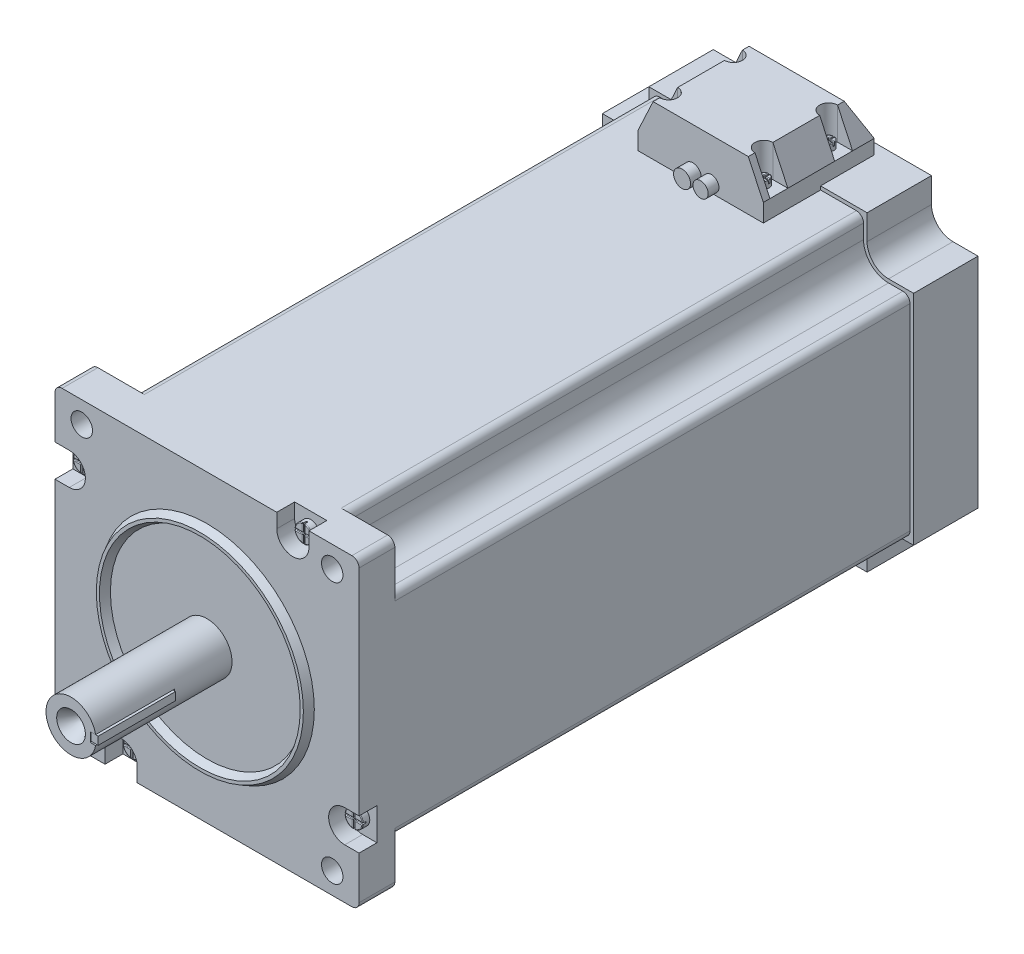
SolidWorks part; units mm, degrees
ref_plane "Front Plane" through (0, 0, 0) normal (0, 0, 1) x (1, 0, 0)
ref_plane "Top Plane" through (0, 0, 0) normal (0, 1, 0) x (1, 0, 0)
ref_plane "Right Plane" through (0, 0, 0) normal (1, 0, 0) x (0, 0, -1)
sketch "Sketch1" plane through (0, 0, 0) normal (0, 0, 1) x (1, 0, 0)
  line L0 (42.5, 85) -> (42.5, 0) construction
  line L1 (13, 0) -> (72, 0)
  line L2 (0, 13) -> (0, 72)
  line L3 (13, 85) -> (72, 85)
  line L4 (85, 13) -> (85, 72)
  line L7 (0, 72) -> (6, 72)
  line L8 (13, 85) -> (13, 79)
  line L9 (0, 42.5) -> (85, 42.5) construction
  line L10 (72, 85) -> (72, 79)
  line L11 (85, 72) -> (79, 72)
  line L14 (13, 0) -> (13, 6)
  line L15 (0, 13) -> (6, 13)
  line L20 (85, 13) -> (79, 13)
  line L21 (72, 0) -> (72, 6)
  arc A0 (13, 79) -> (6, 72) centre (6, 79) cw
  arc A1 (72, 79) -> (79, 72) centre (79, 79) ccw
  arc A2 (13, 6) -> (6, 13) centre (6, 6) ccw
  arc A3 (72, 6) -> (79, 13) centre (79, 6) cw
  point P10 (13, 72)
  point P20 (72, 72)
  point P26 (13, 13)
  point P32 (72, 13)
  dimension "D5" = 7
  dimension "D3" = 13
  dimension "D4" = 13
extrude "Boss-Extrude1" add sketch "Sketch1" along normal blind 144
sketch "Sketch2" plane through (0, 0, 0) normal (0, 0, -1) x (-1, 0, 0)
  line L0 (1, 73) -> (-6, 73)
  line L1 (-12, 79) -> (-12, 86)
  line L2 (-12, 86) -> (-73, 86)
  line L3 (-73, 86) -> (-73, 79)
  line L4 (-79, 73) -> (-86, 73)
  line L5 (-86, 73) -> (-86, 12)
  line L6 (-86, 12) -> (-79, 12)
  line L7 (-73, 6) -> (-73, -1)
  line L8 (-73, -1) -> (-12, -1)
  line L9 (-12, -1) -> (-12, 6)
  line L10 (-6, 12) -> (1, 12)
  line L11 (1, 12) -> (1, 73)
  line L12 (0, 72) -> (-6, 72)
  line L13 (-13, 79) -> (-13, 85)
  line L14 (-13, 85) -> (-72, 85)
  line L15 (-72, 85) -> (-72, 79)
  line L16 (-79, 72) -> (-85, 72)
  line L17 (-85, 72) -> (-85, 13)
  line L18 (-85, 13) -> (-79, 13)
  line L19 (-72, 6) -> (-72, 0)
  line L20 (-72, 0) -> (-13, 0)
  line L21 (-13, 0) -> (-13, 6)
  line L22 (-6, 13) -> (0, 13)
  line L23 (0, 13) -> (0, 72)
  line L24 (0, 72) -> (-6, 72)
  line L25 (-13, 79) -> (-13, 85)
  line L26 (-13, 85) -> (-72, 85)
  line L27 (-72, 85) -> (-72, 79)
  line L28 (-79, 72) -> (-85, 72)
  line L29 (-85, 72) -> (-85, 13)
  line L30 (-85, 13) -> (-79, 13)
  line L31 (-72, 6) -> (-72, 0)
  line L32 (-72, 0) -> (-13, 0)
  line L33 (-13, 0) -> (-13, 6)
  line L34 (-6, 13) -> (0, 13)
  line L35 (0, 13) -> (0, 72)
  arc A0 (-12, 79) -> (-6, 73) centre (-6, 79) ccw
  arc A1 (-79, 73) -> (-73, 79) centre (-79, 79) ccw
  arc A2 (-73, 6) -> (-79, 12) centre (-79, 6) ccw
  arc A3 (-6, 12) -> (-12, 6) centre (-6, 6) ccw
  arc A4 (-13, 79) -> (-6, 72) centre (-6, 79) ccw
  arc A5 (-79, 72) -> (-72, 79) centre (-79, 79) ccw
  arc A6 (-72, 6) -> (-79, 13) centre (-79, 6) ccw
  arc A7 (-6, 13) -> (-13, 6) centre (-6, 6) ccw
  arc A8 (-13, 79) -> (-6, 72) centre (-6, 79) ccw
  arc A9 (-79, 72) -> (-72, 79) centre (-79, 79) ccw
  arc A10 (-72, 6) -> (-79, 13) centre (-79, 6) ccw
  arc A11 (-6, 13) -> (-13, 6) centre (-6, 6) ccw
  line M17 (0, 72) -> (-6, 72)
  arc M18 (-6, 72) -> (-13, 79) centre (-6, 79) cw
  line M19 (-13, 79) -> (-13, 85)
  line M20 (-13, 85) -> (-72, 85)
  line M21 (-72, 85) -> (-72, 79)
  arc M22 (-72, 79) -> (-79, 72) centre (-79, 79) cw
  line M23 (-79, 72) -> (-85, 72)
  line M24 (-85, 72) -> (-85, 13)
  line M25 (-85, 13) -> (-79, 13)
  arc M26 (-79, 13) -> (-72, 6) centre (-79, 6) cw
  line M27 (-72, 6) -> (-72, 0)
  line M28 (-72, 0) -> (-13, 0)
  line M29 (-13, 0) -> (-13, 6)
  arc M30 (-13, 6) -> (-6, 13) centre (-6, 6) cw
  line M31 (-6, 13) -> (0, 13)
  line M32 (0, 13) -> (0, 72)
  dimension "D1" = 0
  dimension "D2" = 1
extrude "Boss-Extrude2" add sketch "Sketch2" along normal blind 18 contours M32 M17 M18 M19 M20 M21 M22 M23 M24 M25 M26 M27 M28 M29 M30 M31 | A3 L10 L11 L0 A0 L1 L2 L3 A1 L4 L5 L6 A2 L7 L8 L9 M17 M32 M31 M30 M29 M28 M27 M26 M25 M24 M23 M22 M21 M20 M19 M18
sketch "Sketch4" plane through (0, 0, 144) normal (0, 0, 1) x (1, 0, 0)
  line L1 (0, 0) -> (85, 0)
  line L2 (0, 0) -> (0, 85)
  line L3 (0, 85) -> (85, 85)
  line L4 (85, 0) -> (85, 85)
  line L5 (0, 0) -> (85, 85) construction
  line L6 (0, 85) -> (85, 0) construction
  point P0 (42.5, 42.5)
extrude "Boss-Extrude3" add sketch "Sketch4" along normal blind 10
sketch "Sketch5" plane through (0, 0, 154) normal (0, 0, 1) x (1, 0, 0)
  line L0 (42.5, 85) -> (42.5, -1) construction
  line L1 (85, 85) -> (0, 85) construction
  line L2 (73, -1) -> (12, -1) construction
  line L3 (0, 42.5) -> (85, 42.5) construction
  line L4 (0, 72) -> (0, 13) construction
  line L5 (85, 0) -> (85, 85) construction
  circle A0 centre (7.5, 79) radius 3
  circle A1 centre (77.5, 79) radius 3
  circle A2 centre (77.5, 6) radius 3
  circle A3 centre (7.5, 6) radius 3
  dimension "D1" = 6
  dimension "D2" = 35
  dimension "D3" = 6
extrude "Cut-Extrude1" cut sketch "Sketch5" against normal up to surface (10 mm away) up to face at (6.6899, 78.3101, 144)
sketch "Sketch6" plane through (0, 0, 154) normal (0, 0, 1) x (1, 0, 0)
  line L0 (0, 71) -> (4, 71)
  line L1 (0, 72) -> (0, 13) construction
  line L2 (85, 85) -> (0, 85) construction
  line L3 (0, 62) -> (4, 62)
  line L4 (0, 71) -> (0, 62)
  line L5 (62, 85) -> (62, 81)
  line L6 (71, 85) -> (71, 81)
  line L7 (71, 85) -> (62, 85)
  line L8 (85, 23) -> (81, 23)
  line L9 (85, 14) -> (81, 14)
  line L10 (85, 14) -> (85, 23)
  line L11 (23, 0) -> (23, 4)
  line L12 (14, 0) -> (14, 4)
  line L13 (14, 0) -> (23, 0)
  arc A0 (4, 62) -> (4, 71) centre (4, 66.5) ccw
  circle A1 centre (42.5, 42.5) radius 6.3473 construction
  arc A2 (62, 81) -> (71, 81) centre (66.5, 81) ccw
  arc A3 (81, 23) -> (81, 14) centre (81, 18.5) ccw
  arc A4 (23, 4) -> (14, 4) centre (18.5, 4) ccw
  point P29 (42.5, 42.5)
  dimension "D1" = 14
  dimension "D3" = 4
  dimension "D2" = 9
  dimension "D4" = 4
extrude "Cut-Extrude2" cut sketch "Sketch6" against normal blind 5
sketch "Sketch7" plane through (0, 0, 154) normal (0, 0, 1) x (1, 0, 0)
  circle A0 centre (42.5, 42.5) radius 30
  circle A1 centre (42.5, 42.5) radius 27
  dimension "D1" = 60
  dimension "D2" = 3
extrude "Boss-Extrude4" add sketch "Sketch7" along normal blind 2 draft 28
sketch "Sketch8" plane through (0, 0, 154) normal (0, 0, 1) x (1, 0, 0)
  circle A0 centre (42.5, 42.5) radius 7
  dimension "D1" = 14
extrude "Boss-Extrude5" add sketch "Sketch8" along normal blind 38
sketch "Sketch9" plane through (0, 0, 192) normal (0, 0, 1) x (1, 0, 0)
  circle A0 centre (42.5, 42.5) radius 4.0146
extrude "Cut-Extrude3" cut sketch "Sketch9" against normal blind 5 draft 32
sketch "Sketch10" plane through (0, 0, 192) normal (0, 0, 1) x (1, 0, 0)
  line L1 (47.8876, 43.8537) -> (49.7957, 43.8537)
  line L2 (47.8876, 43.8537) -> (47.8876, 41.2149)
  line L3 (47.8876, 41.2149) -> (49.7957, 41.2149)
  line L4 (49.7957, 43.8537) -> (49.7957, 41.2149)
extrude "Cut-Extrude4" cut sketch "Sketch10" against normal blind 22
sketch "Sketch11" plane through (47.8876, 0, 0) normal (1, 0, 0) x (0, 0, -1)
  line L8 (-191.8, 43.6537) -> (-191.8, 41.4149)
  line L9 (-191.8, 41.4149) -> (-170.2, 41.4149)
  line L10 (-170.2, 41.4149) -> (-170.2, 43.6537)
  line L11 (-170.2, 43.6537) -> (-191.8, 43.6537)
  line L12 (-191.8, 43.6537) -> (-191.8, 41.4149)
  line L13 (-191.8, 41.4149) -> (-170.2, 41.4149)
  line L14 (-170.2, 41.4149) -> (-170.2, 43.6537)
  line L15 (-170.2, 43.6537) -> (-191.8, 43.6537)
  dimension "D1" = 0.2
extrude "Boss-Extrude6" add sketch "Sketch11" along normal blind 2
fillet "Fillet1" radius 2 4 edges at (85, 0, 149) (0, 0, 149) (0, 85, 149) (85, 85, 149)
fillet "Fillet2" radius 2 8 edges at (0, 13, 72) (13, 0, 72) (72, 0, 72) (85, 13, 72) (0, 72, 72) (85, 72, 72) (13, 85, 72) (72, 85, 72)
sketch "Sketch12" plane through (0, 0, 149) normal (0, 0, 1) x (1, 0, 0)
  circle A0 centre (66.5, 80.4984) radius 2.5
  circle A1 centre (80.4984, 18.5) radius 2.5
  circle A2 centre (18.5, 4.5016) radius 2.5
  circle A3 centre (4.5016, 66.5) radius 2.5
  point P11 (42.5, 42.5)
  dimension "D1" = 5
  dimension "D2" = 4
extrude "Boss-Extrude7" add sketch "Sketch12" along normal blind 2
sketch "Sketch13" plane through (0, 0, 151) normal (0, 0, 1) x (1, 0, 0)
  line L0 (66.5, 82.9984) -> (66.5, 77.9984) construction
  line L1 (64, 80.4984) -> (69, 80.4984) construction
  line L2 (64, 80.2984) -> (66.3, 80.2984)
  line L3 (66.3, 82.9984) -> (66.3, 80.6984)
  line L4 (64, 80.6984) -> (66.3, 80.6984)
  line L5 (66.7, 82.9984) -> (66.7, 80.6984)
  line L6 (66.3, 80.2984) -> (66.3, 77.9984)
  line L7 (66.7, 80.6984) -> (69, 80.6984)
  line L8 (66.3, 82.9984) -> (66.3, 77.9984) construction
  line L9 (66.7, 80.2984) -> (66.7, 77.9984)
  line L10 (64, 80.6984) -> (69, 80.6984) construction
  line L11 (66.7, 80.2984) -> (69, 80.2984)
  line L12 (66.7, 82.9984) -> (66.7, 77.9984) construction
  line L13 (82.9984, 18.3) -> (80.6984, 18.3)
  line L14 (64, 80.2984) -> (69, 80.2984) construction
  line L15 (80.6984, 18.3) -> (80.6984, 16)
  line L16 (80.2984, 18.3) -> (80.2984, 16)
  line L17 (80.2984, 18.3) -> (77.9984, 18.3)
  line L18 (80.2984, 18.7) -> (77.9984, 18.7)
  line L19 (80.2984, 21) -> (80.2984, 18.7)
  line L20 (80.6984, 21) -> (80.6984, 18.7)
  line L21 (82.9984, 18.7) -> (80.6984, 18.7)
  line L22 (18.3, 2.0016) -> (18.3, 4.3016)
  line L23 (18.3, 4.3016) -> (16, 4.3016)
  line L24 (18.3, 4.7016) -> (16, 4.7016)
  line L25 (18.3, 4.7016) -> (18.3, 7.0016)
  line L26 (18.7, 4.7016) -> (18.7, 7.0016)
  line L27 (21, 4.7016) -> (18.7, 4.7016)
  line L28 (21, 4.3016) -> (18.7, 4.3016)
  line L29 (18.7, 2.0016) -> (18.7, 4.3016)
  line L30 (2.0016, 66.7) -> (4.3016, 66.7)
  line L31 (4.3016, 66.7) -> (4.3016, 69)
  line L32 (4.7016, 66.7) -> (4.7016, 69)
  line L33 (4.7016, 66.7) -> (7.0016, 66.7)
  line L34 (4.7016, 66.3) -> (7.0016, 66.3)
  line L35 (4.7016, 64) -> (4.7016, 66.3)
  line L36 (4.3016, 64) -> (4.3016, 66.3)
  line L37 (2.0016, 66.3) -> (4.3016, 66.3)
  circle A0 centre (66.5, 80.4984) radius 2.5 construction
  circle A1 centre (66.5, 80.4984) radius 2.5 construction
  circle A2 centre (80.4984, 18.5) radius 2.5
  circle A3 centre (66.5, 80.4984) radius 2.5
  circle A4 centre (66.5, 80.4984) radius 2.5
  circle A5 centre (18.5, 4.5016) radius 2.5
  circle A6 centre (4.5016, 66.5) radius 2.5
  point P69 (42.5, 42.5)
  circle M4 centre (66.5, 80.4984) radius 2.5
  dimension "D1" = 0.2
  dimension "D2" = 0.2
  dimension "D3" = 0
  dimension "D4" = 4
extrude "Cut-Extrude5" cut sketch "Sketch13" against normal blind 1 contours L9 L11 L7 L5 L3 L4 L2 L6 M4 | L32 A6 L31 L30 L37 L36 L35 L34 L33 | L26 A5 L25 L24 L23 L22 L29 L28 L27 | L20 A2 L19 L18 L17 L16 L15 L13 L21
fillet "Fillet3" radius 0.2 48 edges at (3.1556, 66.3, 151) (4.3016, 65.154, 151) (2.7338, 64.7322, 151) (6.2694, 64.7322, 151) (4.7016, 65.154, 151) (5.8476, 66.3, 151) (6.2694, 68.2678, 151) (5.8476, 66.7, 151) (4.7016, 67.846, 151) (4.3016, 67.846, 151) (3.1556, 66.7, 151) (2.7338, 68.2678, 151) (20.2678, 6.2694, 151) (19.846, 4.7016, 151) (18.7, 5.8476, 151) (18.7, 3.1556, 151) (19.846, 4.3016, 151) (20.2678, 2.7338, 151) (17.154, 4.3016, 151) (18.3, 3.1556, 151) (16.7322, 2.7338, 151) (16.7322, 6.2694, 151) (18.3, 5.8476, 151) (17.154, 4.7016, 151) (78.7306, 16.7322, 151) (79.1524, 18.3, 151) (80.2984, 17.154, 151) (80.6984, 17.154, 151) (81.8444, 18.3, 151) (82.2662, 16.7322, 151) (81.8444, 18.7, 151) (80.6984, 19.846, 151) (82.2662, 20.2678, 151) (78.7306, 20.2678, 151) (80.2984, 19.846, 151) (79.1524, 18.7, 151) (68.2678, 78.7306, 151) (66.7, 79.1524, 151) (67.846, 80.2984, 151) (64.7322, 78.7306, 151) (65.154, 80.2984, 151) (66.3, 79.1524, 151) (66.3, 81.8444, 151) (65.154, 80.6984, 151) (64.7322, 82.2662, 151) (67.846, 80.6984, 151) (66.7, 81.8444, 151) (68.2678, 82.2662, 151)
sketch "Sketch14" plane through (0, 85, 0) normal (0, 1, 0) x (1, 0, 0)
  line L0 (42.5, 18) -> (42.5, -26.4947) construction
  line L1 (12, 18) -> (73, 18) construction
  line L3 (25, 15) -> (60, 15)
  line L4 (25, 15) -> (25, -16)
  line L5 (25, -16) -> (60, -16)
  line L6 (60, 15) -> (60, -16)
  line L7 (25, 15) -> (60, -16) construction
  line L8 (25, -16) -> (60, 15) construction
  point P4 (42.5, -0.5)
  dimension "D1" = 35
  dimension "D2" = 31
  dimension "D3" = 3
extrude "Boss-Extrude8" add sketch "Sketch14" along normal blind 5
sketch "Sketch15" plane through (0, 90, 0) normal (0, 1, 0) x (1, 0, 0)
  line L4 (60, -16) -> (60, 15)
  line L5 (60, 15) -> (25, 15)
  line L6 (25, 15) -> (25, -16)
  line L7 (25, -16) -> (60, -16)
  line L8 (60, -16) -> (60, 15)
  line L9 (60, 15) -> (25, 15)
  line L10 (25, 15) -> (25, -16)
  line L11 (25, -16) -> (60, -16)
  dimension "D1" = 0
extrude "Boss-Extrude9" add sketch "Sketch15" along normal blind 9 draft 25
sketch "Sketch16" plane through (0, 99, 0) normal (0, 1, 0) x (1, 0, 0)
  line L0 (25, 0) -> (25, -16) construction
  line L1 (25, -11.8032) -> (60, -11.8032)
  line L2 (25, -11.8032) -> (25, -16)
  line L3 (25, -16) -> (60, -16)
  line L4 (60, -11.8032) -> (60, -16)
  line L5 (29.1968, -11.8032) -> (55.8032, -11.8032) construction
extrude "Boss-Extrude10" add sketch "Sketch16" against normal up to surface (14 mm away) up to face at (48.5, 85, 95.125)
sketch "Sketch17" plane through (0, 0, 11.8032) normal (0, 0, -1) x (-1, 0, 0)
  line L3 (-60, 90) -> (-55.8032, 99)
  line L4 (-55.8032, 99) -> (-60, 99)
  line L5 (-60, 99) -> (-60, 90)
  line L6 (-60, 90) -> (-55.8032, 99)
  line L7 (-55.8032, 99) -> (-60, 99)
  line L8 (-60, 99) -> (-60, 90)
  line L9 (-29.1968, 99) -> (-25, 90)
  line L10 (-25, 90) -> (-25, 99)
  line L11 (-25, 99) -> (-29.1968, 99)
  line L12 (-29.1968, 99) -> (-25, 90)
  line L13 (-25, 90) -> (-25, 99)
  line L14 (-25, 99) -> (-29.1968, 99)
  dimension "D1" = 0
  dimension "D2" = 0
extrude "Cut-Extrude6" cut sketch "Sketch17" against normal up to surface (4.1968 mm away) up to face at (42.5, 92, 16)
sketch "Sketch18" plane through (0, 99, 0) normal (0, 1, 0) x (1, 0, 0)
  line L0 (42.5, 10.8032) -> (42.5, -16) construction
  line L1 (55.8032, 10.8032) -> (29.1968, 10.8032) construction
  line L2 (29.1968, -16) -> (55.8032, -16) construction
  line L3 (29.1968, -2.5984) -> (55.8032, -2.5984) construction
  line L4 (29.1968, 10.8032) -> (29.1968, -16) construction
  line L5 (55.8032, -16) -> (55.8032, 10.8032) construction
  circle A0 centre (55.8032, 6.4489) radius 2.5
  circle A1 centre (29.1968, 6.4489) radius 2.5
  circle A2 centre (29.1968, -11.6457) radius 2.5
  circle A3 centre (55.8032, -11.6457) radius 2.5
  dimension "D1" = 5
extrude "Cut-Extrude7" cut sketch "Sketch18" against normal blind 9
sketch "Sketch19" plane through (0, 99, 0) normal (0, 1, 0) x (1, 0, 0)
  line L1 (55.8032, -14.1457) -> (60.3281, -14.1457)
  line L2 (55.8032, -14.1457) -> (55.8032, -9.1457)
  line L3 (55.8032, -9.1457) -> (60.3281, -9.1457)
  line L4 (60.3281, -14.1457) -> (60.3281, -9.1457)
  line L5 (55.8032, 3.9489) -> (61.0899, 3.9489)
  line L6 (55.8032, 3.9489) -> (55.8032, 8.9489)
  line L7 (55.8032, 8.9489) -> (61.0899, 8.9489)
  line L8 (61.0899, 3.9489) -> (61.0899, 8.9489)
  line L9 (29.1968, 3.9489) -> (24.0199, 3.9489)
  line L10 (29.1968, 3.9489) -> (29.1968, 8.9489)
  line L11 (29.1968, 8.9489) -> (24.0199, 8.9489)
  line L12 (24.0199, 3.9489) -> (24.0199, 8.9489)
  line L13 (29.1968, -14.1457) -> (23.5175, -14.1457)
  line L14 (29.1968, -14.1457) -> (29.1968, -9.1457)
  line L15 (29.1968, -9.1457) -> (23.5175, -9.1457)
  line L16 (23.5175, -14.1457) -> (23.5175, -9.1457)
extrude "Cut-Extrude8" cut sketch "Sketch19" against normal blind 9
sketch "Sketch20" plane through (0, 90, 0) normal (0, 1, 0) x (1, 0, 0)
  circle A0 centre (55.8032, 6.4489) radius 1.5
  circle A1 centre (55.8032, -11.6457) radius 1.5
  circle A2 centre (29.1968, -11.6457) radius 1.5
  circle A3 centre (29.1968, 6.4489) radius 1.5
  dimension "D1" = 3
extrude "Boss-Extrude11" add sketch "Sketch20" along normal blind 2
sketch "Sketch21" plane through (0, 92, 0) normal (0, 1, 0) x (1, 0, 0)
  line L0 (29.1968, 7.9489) -> (29.1968, 4.9489) construction
  line L1 (27.6968, 6.4489) -> (30.6968, 6.4489) construction
  line L2 (27.6968, 6.2489) -> (28.9968, 6.2489)
  line L3 (28.9968, 7.9489) -> (28.9968, 6.6489)
  line L4 (27.6968, 6.6489) -> (28.9968, 6.6489)
  line L5 (29.3968, 7.9489) -> (29.3968, 6.6489)
  line L6 (29.3968, 6.2489) -> (29.3968, 4.9489)
  line L7 (29.3968, 6.6489) -> (30.6968, 6.6489)
  line L8 (29.3968, 7.9489) -> (29.3968, 4.9489) construction
  line L9 (28.9968, 6.2489) -> (28.9968, 4.9489)
  line L10 (27.6968, 6.6489) -> (30.6968, 6.6489) construction
  line L11 (29.3968, 6.2489) -> (30.6968, 6.2489)
  line L12 (28.9968, 7.9489) -> (28.9968, 4.9489) construction
  line L13 (42.5, 10.8032) -> (42.5, 3.8934) construction
  line L14 (27.6968, 6.2489) -> (30.6968, 6.2489) construction
  line L15 (55.8032, 10.8032) -> (29.1968, 10.8032) construction
  line L16 (29.1968, -2.5984) -> (34.7987, -2.5984) construction
  line L17 (29.1968, 3.9489) -> (29.1968, -9.1457) construction
  line L18 (57.3032, 6.4489) -> (54.3032, 6.4489) construction
  line L19 (55.8032, 7.9489) -> (55.8032, 4.9489) construction
  line L20 (55.6032, 6.2489) -> (54.3032, 6.2489)
  line L21 (56.0032, 6.2489) -> (56.0032, 4.9489)
  line L22 (55.6032, 6.6489) -> (54.3032, 6.6489)
  line L23 (55.6032, 6.2489) -> (55.6032, 4.9489)
  line L24 (55.6032, 7.9489) -> (55.6032, 6.6489)
  line L25 (57.3032, 6.6489) -> (56.0032, 6.6489)
  line L26 (56.0032, 7.9489) -> (56.0032, 6.6489)
  line L27 (57.3032, 6.2489) -> (56.0032, 6.2489)
  line L28 (55.8032, -13.1457) -> (55.8032, -10.1457) construction
  line L29 (57.3032, -11.6457) -> (54.3032, -11.6457) construction
  line L30 (42.5, -16) -> (42.5, -9.0901) construction
  line L31 (27.6968, -11.6457) -> (30.6968, -11.6457) construction
  line L32 (29.1968, -13.1457) -> (29.1968, -10.1457) construction
  line L33 (57.3032, -11.4457) -> (56.0032, -11.4457)
  line L34 (56.0032, -13.1457) -> (56.0032, -11.8457)
  line L35 (57.3032, -11.8457) -> (56.0032, -11.8457)
  line L36 (55.6032, -13.1457) -> (55.6032, -11.8457)
  line L37 (55.6032, -11.4457) -> (55.6032, -10.1457)
  line L38 (55.6032, -11.8457) -> (54.3032, -11.8457)
  line L39 (56.0032, -11.4457) -> (56.0032, -10.1457)
  line L40 (55.6032, -11.4457) -> (54.3032, -11.4457)
  line L41 (29.3968, -11.4457) -> (30.6968, -11.4457)
  line L42 (28.9968, -11.4457) -> (28.9968, -10.1457)
  line L43 (29.3968, -11.8457) -> (30.6968, -11.8457)
  line L44 (29.3968, -11.4457) -> (29.3968, -10.1457)
  line L45 (29.3968, -13.1457) -> (29.3968, -11.8457)
  line L46 (27.6968, -11.8457) -> (28.9968, -11.8457)
  line L47 (28.9968, -13.1457) -> (28.9968, -11.8457)
  line L48 (27.6968, -11.4457) -> (28.9968, -11.4457)
  circle A0 centre (29.1968, 6.4489) radius 1.5 construction
  circle A1 centre (29.1968, 6.4489) radius 1.5 construction
  arc A2 (28.9968, 4.9623) -> (29.3968, 4.9623) centre (29.1968, 6.4489) ccw
  circle A3 centre (29.1968, 6.4489) radius 1.5
  arc A4 (27.7102, 6.6489) -> (27.7102, 6.2489) centre (29.1968, 6.4489) ccw
  arc A5 (30.6834, 6.2489) -> (30.6834, 6.6489) centre (29.1968, 6.4489) ccw
  arc A6 (29.3968, 7.9355) -> (28.9968, 7.9355) centre (29.1968, 6.4489) ccw
  arc A7 (55.6032, 7.9355) -> (56.0032, 7.9355) centre (55.8032, 6.4489) cw
  arc A8 (54.3166, 6.2489) -> (54.3166, 6.6489) centre (55.8032, 6.4489) cw
  arc A9 (57.2898, 6.6489) -> (57.2898, 6.2489) centre (55.8032, 6.4489) cw
  arc A10 (56.0032, 4.9623) -> (55.6032, 4.9623) centre (55.8032, 6.4489) cw
  arc A11 (56.0032, -10.1591) -> (55.6032, -10.1591) centre (55.8032, -11.6457) ccw
  arc A12 (57.2898, -11.8457) -> (57.2898, -11.4457) centre (55.8032, -11.6457) ccw
  arc A13 (54.3166, -11.4457) -> (54.3166, -11.8457) centre (55.8032, -11.6457) ccw
  arc A14 (55.6032, -13.1323) -> (56.0032, -13.1323) centre (55.8032, -11.6457) ccw
  arc A15 (29.3968, -13.1323) -> (28.9968, -13.1323) centre (29.1968, -11.6457) cw
  arc A16 (30.6834, -11.4457) -> (30.6834, -11.8457) centre (29.1968, -11.6457) cw
  arc A17 (27.7102, -11.8457) -> (27.7102, -11.4457) centre (29.1968, -11.6457) cw
  arc A18 (28.9968, -10.1591) -> (29.3968, -10.1591) centre (29.1968, -11.6457) cw
  circle M6 centre (29.1968, 6.4489) radius 1.5
  dimension "D1" = 0.2
  dimension "D2" = 0.2
  dimension "D3" = 0
extrude "Cut-Extrude9" cut sketch "Sketch21" against normal blind 1 contours A18 L42 L48 A17 L46 L47 A15 L45 L43 A16 L41 L44 | L6 L11 L7 L5 L3 L4 L2 L9 M6 | L36 A14 L34 L35 A12 L33 L39 A11 L37 L40 A13 L38 | A10 L21 L27 A9 L25 L26 A7 L24 L22 A8 L20 L23
fillet "Fillet4" radius 0.2 48 edges at (28.3535, 92, 11.8457) (28.9968, 92, 12.489) (28.1361, 92, 12.7064) (30.2574, 92, 12.7064) (29.3968, 92, 12.489) (30.0401, 92, 11.8457) (30.2574, 92, 10.585) (30.0401, 92, 11.4457) (29.3968, 92, 10.8024) (28.9968, 92, 10.8024) (28.3535, 92, 11.4457) (28.1361, 92, 10.585) (28.1361, 92, -5.3883) (28.3535, 92, -6.2489) (28.9968, 92, -5.6056) (30.2574, 92, -5.3883) (29.3968, 92, -5.6056) (30.0401, 92, -6.2489) (30.0401, 92, -6.6489) (29.3968, 92, -7.2922) (30.2574, 92, -7.5096) (28.9968, 92, -7.2922) (28.3535, 92, -6.6489) (28.1361, 92, -7.5096) (56.6465, 92, -6.6489) (56.0032, 92, -7.2922) (56.8639, 92, -7.5096) (56.0032, 92, -5.6056) (56.6465, 92, -6.2489) (56.8639, 92, -5.3883) (54.7426, 92, -5.3883) (54.9599, 92, -6.2489) (55.6032, 92, -5.6056) (54.7426, 92, -7.5096) (55.6032, 92, -7.2922) (54.9599, 92, -6.6489) (56.8639, 92, 10.585) (56.6465, 92, 11.4457) (56.0032, 92, 10.8024) (54.7426, 92, 10.585) (55.6032, 92, 10.8024) (54.9599, 92, 11.4457) (54.9599, 92, 11.8457) (55.6032, 92, 12.489) (54.7426, 92, 12.7064) (56.0032, 92, 12.489) (56.6465, 92, 11.8457) (56.8639, 92, 12.7064)
sketch "Sketch22" plane through (0, 0, 16) normal (0, 0, 1) x (1, 0, 0)
  circle A0 centre (40.2888, 87.3656) radius 2.3726
  circle A1 centre (45.4594, 87.3656) radius 2.1286
extrude "Boss-Extrude12" add sketch "Sketch22" along normal blind 3
